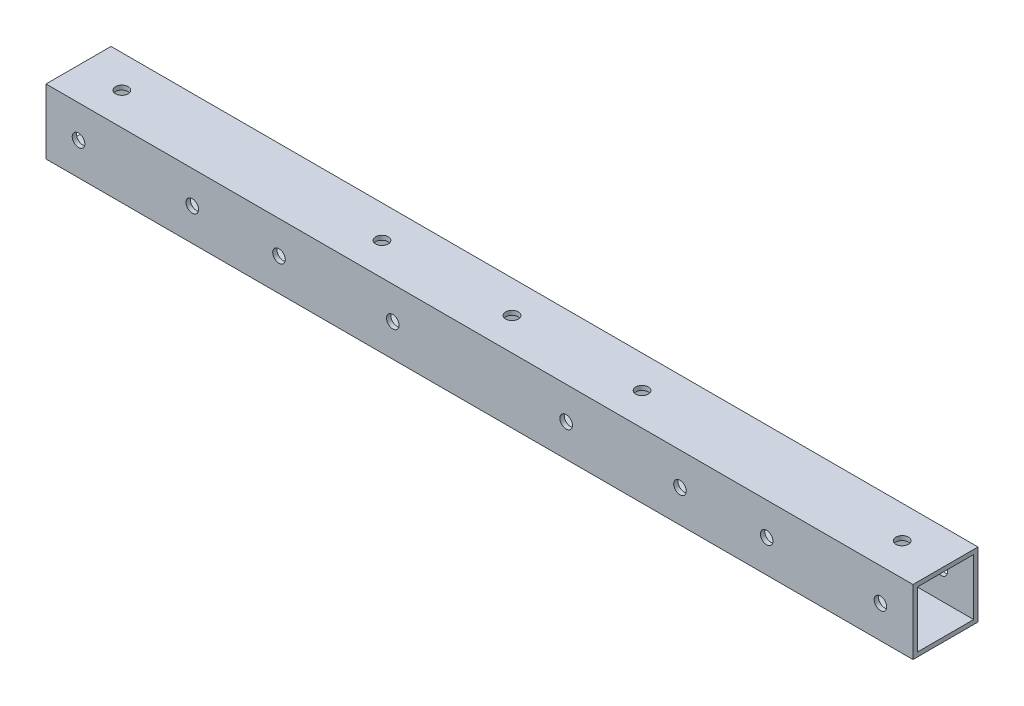
SolidWorks part; units mm, degrees
material "Thornel Mat VMA"
ref_plane "前视基准面" through (0, 0, 0) normal (0, 0, 1) x (1, 0, 0)
ref_plane "上视基准面" through (0, 0, 0) normal (0, 1, 0) x (1, 0, 0)
ref_plane "右视基准面" through (0, 0, 0) normal (1, 0, 0) x (0, 0, -1)
other "Configuration Table"
sketch "草图1" plane through (0, 0, 0) normal (0, 1, 0) x (1, 0, 0)
  line L0 (0, 0) -> (200, 0)
  dimension "D1" = 200
other "铝管 15X15X1(1)"
ref_plane "基准面1" through (0, 0, 0) normal (1, 0, 0) x (0, 0, -1)
sketch "草图11" plane through (0, 0, 0) normal (1, 0, 0) x (0, 0, -1)
  line L1 (-7.5, -7.5) -> (7.5, -7.5)
  line L2 (-7.5, -7.5) -> (-7.5, 7.5)
  line L3 (-7.5, 7.5) -> (7.5, 7.5)
  line L4 (7.5, -7.5) -> (7.5, 7.5)
  line L5 (-7.5, -7.5) -> (7.5, 7.5) construction
  line L6 (-7.5, 7.5) -> (7.5, -7.5) construction
  line L7 (-6.5, -6.5) -> (6.5, -6.5)
  line L8 (-6.5, -6.5) -> (-6.5, 6.5)
  line L9 (-6.5, 6.5) -> (6.5, 6.5)
  line L10 (6.5, -6.5) -> (6.5, 6.5)
  line L11 (-6.5, -6.5) -> (6.5, 6.5) construction
  line L12 (-6.5, 6.5) -> (6.5, -6.5) construction
  point P0 (0, 0)
  point P6 (0, 0)
  point P11 (0, 0)
  dimension "D1" = 15
  dimension "D2" = 15
  dimension "D3" = 13
  dimension "D4" = 13
sketch "草图12" plane through (0, 7.5, 0) normal (0, -1, 0) x (-1, 0, 0)
  line L0 (0, 0) -> (-200, 0) construction
  line L3 (0, -7.5) -> (0, 7.5) construction
  line L4 (-200, -7.5) -> (-200, 7.5) construction
  circle A0 centre (-100, 0) radius 1.45
  circle A1 centre (-190, 0) radius 1.45
  circle A2 centre (-10, 0) radius 1.45
  dimension "D1" = 2.9
  dimension "D2" = 2.9
  dimension "D3" = 2.9
  dimension "D4" = 10
  dimension "D5" = 10
extrude "切除-拉伸2" cut sketch "草图12" along normal through all
sketch "草图13" plane through (0, 0, 7.5) normal (0, 0, 1) x (1, 0, 0)
  line L0 (0, 0) -> (200, 0) construction
  line L2 (100, 7.5) -> (100, -7.5) construction
  line L3 (200, 7.5) -> (0, 7.5) construction
  line L4 (200, -7.5) -> (0, -7.5) construction
  circle A0 centre (7.5, 0) radius 1.45
  circle A2 centre (33.75, 0) radius 1.45
  circle A3 centre (53.75, 0) radius 1.45
  circle A4 centre (146.25, 0) radius 1.45
  circle A5 centre (166.25, 0) radius 1.45
  circle A6 centre (192.5, 0) radius 1.45
  dimension "D1" = 2.9
  dimension "D3" = 7.5
  dimension "D5" = 2.9
  dimension "D6" = 2.9
  dimension "D7" = 26.25
  dimension "D8" = 20
extrude "切除-拉伸3" cut sketch "草图13" against normal through all
sketch "草图14" plane through (0, 0, 7.5) normal (0, 0, 1) x (1, 0, 0)
  line L0 (100, 7.5) -> (100, -7.5) construction
  line L1 (200, 7.5) -> (0, 7.5) construction
  line L2 (200, -7.5) -> (0, -7.5) construction
  line L3 (0, 0) -> (200, 0) construction
  circle A0 centre (80, 0) radius 1.45
  circle A1 centre (120, 0) radius 1.45
  dimension "D1" = 2.9
  dimension "D2" = 2.9
  dimension "D3" = 20
  dimension "D4" = 20
extrude "切除-拉伸4" cut sketch "草图14" against normal through all
sketch "草图15" plane through (0, 7.5, 0) normal (0, 1, 0) x (1, 0, 0)
  line L0 (0, 0) -> (200, 0) construction
  circle A0 centre (70, 0) radius 1.45
  circle A1 centre (10, 0) radius 1.45 construction
  circle A2 centre (130, 0) radius 1.45
  circle A3 centre (190, 0) radius 1.45 construction
  dimension "D1" = 2.9
  dimension "D2" = 60
  dimension "D3" = 2.9
  dimension "D4" = 60
extrude "切除-拉伸5" cut sketch "草图15" against normal through all
